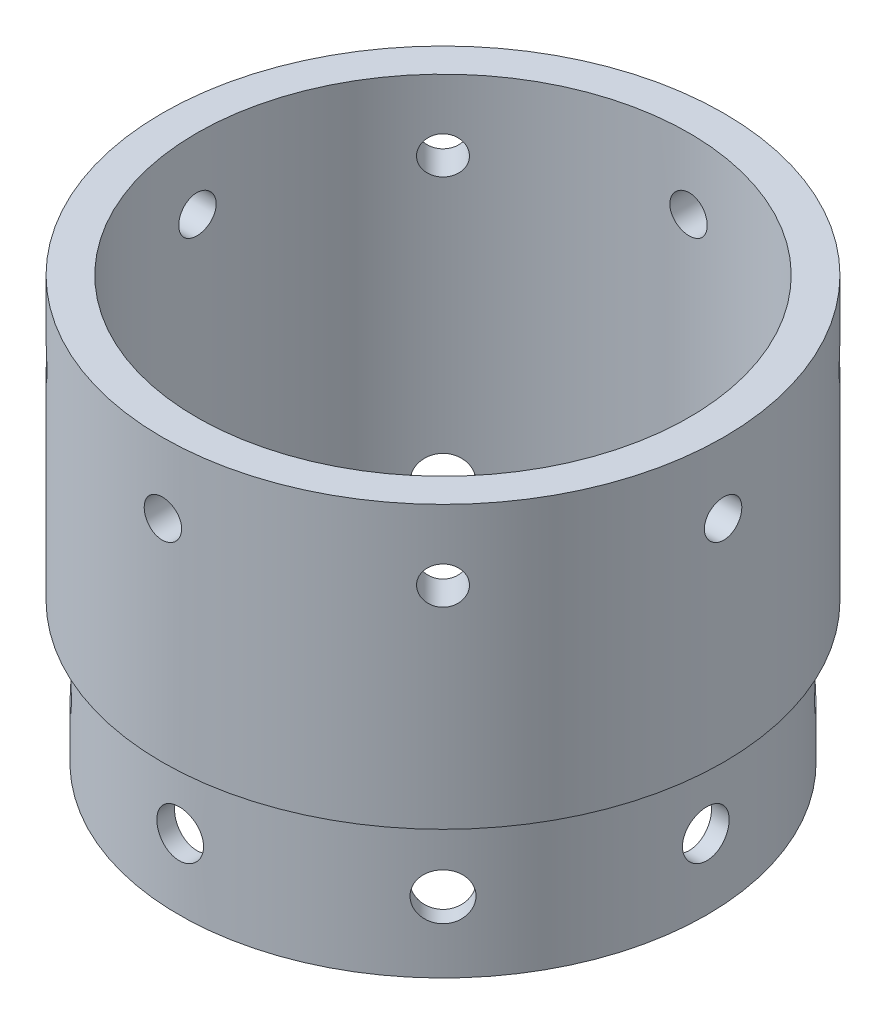
SolidWorks part; units mm, degrees
material "6061-T6 (SS)"
ref_plane "Front Plane" through (0, 0, 0) normal (0, 0, 1) x (1, 0, 0)
ref_plane "Top Plane" through (0, 0, 0) normal (0, 1, 0) x (1, 0, 0)
ref_plane "Right Plane" through (0, 0, 0) normal (1, 0, 0) x (0, 0, -1)
sketch "Sketch1" plane through (0, 0, 0) normal (0, 0, 1) x (1, 0, 0)
  line L0 (0, 77.8484) -> (0, -41.4736) construction
  line L1 (47.625, 0) -> (47.625, 25.4)
  line L2 (47.625, 25.4) -> (50.673, 25.4)
  line L3 (50.673, 25.4) -> (50.673, 76.2)
  line L4 (50.673, 76.2) -> (44.45, 76.2)
  line L5 (44.45, 76.2) -> (44.45, 0)
  line L6 (44.45, 0) -> (47.625, 0)
  dimension "D1" = 25.4
  dimension "D2" = 50.8
  dimension "D3" = 101.346
  dimension "D4" = 95.25
  dimension "D5" = 88.9
revolve "Revolve1" add sketch "Sketch1" angle 360 about L0
ref_plane "Plane1" through (0, 0, 50.673) normal (0, 0, 1) x (1, 0, 0)
hole_wizard "5/16 Clearance Hole1" positions "Sketch2" profile "Sketch4" hole size "5/16" standard "ANSI Inch"
sketch "Sketch2" plane through (0, 0, 50.673) normal (0, 0, 1) x (1, 0, 0)
  line L0 (-47.625, 0) -> (47.625, 0) construction
  point P0 (0, 12.7)
  dimension "D1" = 12.7
sketch "Sketch4" plane through (0, 12.7, 50.673) normal (1, 0, 0) x (0, -1, 0)
  line L0 (0, 0) -> (0, 19.304)
  line L1 (0, 19.304) -> (4.2164, 16.7705)
  line L2 (4.2164, 16.7705) -> (4.2164, 0)
  line L5 (4.2164, 0) -> (0, 0)
  line L10 (0, 19.304) -> (-4.2164, 16.7705) construction
  line L11 (0, -6.35) -> (0, 107.95) construction
  dimension "Hole Dia." = 8.4328
  dimension "Hole Depth" = 19.304
  dimension "Drill Angle" = 118
hole_wizard "1/4 Clearance Hole1" positions "Sketch6" profile "Sketch5" hole size "1/4" standard "ANSI Inch"
sketch "Sketch6" plane through (0, 0, 50.673) normal (0, 0, 1) x (1, 0, 0)
  line L0 (50.673, 76.2) -> (-50.673, 76.2) construction
  point P0 (0, 63.5)
  dimension "D1" = 12.7
sketch "Sketch5" plane through (0, 63.5, 50.673) normal (1, 0, 0) x (0, -1, 0)
  line L0 (0, 0) -> (0, 16.51)
  line L1 (0, 16.51) -> (3.3782, 14.4802)
  line L2 (3.3782, 14.4802) -> (3.3782, 0)
  line L5 (3.3782, 0) -> (0, 0)
  line L10 (0, 16.51) -> (-3.3782, 14.4802) construction
  line L11 (0, -6.35) -> (0, 107.95) construction
  dimension "Hole Dia." = 6.7564
  dimension "Hole Depth" = 16.51
  dimension "Drill Angle" = 118
pattern_circular "CirPattern1" count 8 over 360 about axis through (0, 77.8484, 0) along (0, 1, 0) of "1/4 Clearance Hole1", "5/16 Clearance Hole1"
